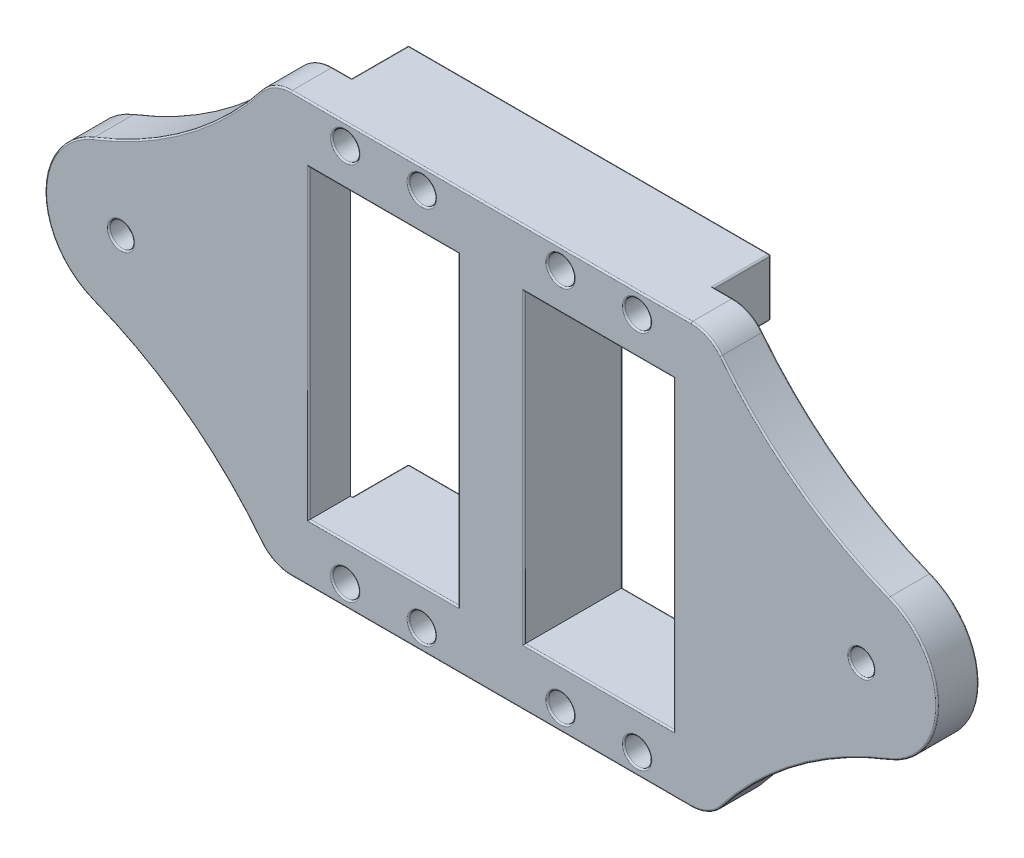
SolidWorks part; units mm, degrees
ref_plane "정면" through (0, 0, 0) normal (0, 0, 1) x (1, 0, 0)
ref_plane "윗면" through (0, 0, 0) normal (0, 1, 0) x (1, 0, 0)
ref_plane "우측면" through (0, 0, 0) normal (1, 0, 0) x (0, 0, -1)
sketch "스케치1" plane through (0, 0, 0) normal (0, 0, 1) x (1, 0, 0)
  line L0 (0, 0) -> (37.5737, 0) construction
  line L1 (4.5, -20) -> (4.5, 20)
  line L2 (4.5, 20) -> (23.9, 20)
  line L3 (4.5, -20) -> (23.9, -20)
  line L4 (23.9, 20) -> (23.9, 27.7)
  line L5 (23.9, -20) -> (23.9, -27.7)
  line L6 (23.9, 27.7) -> (-23.9, 27.7)
  line L7 (23.9, -27.7) -> (-23.9, -27.7)
  line L8 (0, -34.9912) -> (0, 34.9912) construction
  line L9 (-23.9, -20) -> (-23.9, -27.7)
  line L10 (-4.5, -20) -> (-23.9, -20)
  line L11 (-23.9, 20) -> (-23.9, 27.7)
  line L12 (-4.5, 20) -> (-23.9, 20)
  line L13 (-4.5, -20) -> (-4.5, 20)
  circle A0 centre (19.25, 25) radius 1.1
  circle A1 centre (19.25, -25) radius 1.1
  circle A2 centre (9.15, 25) radius 1.1
  circle A3 centre (9.15, -25) radius 1.1
  circle A4 centre (-9.15, -25) radius 1.1
  circle A5 centre (-19.25, -25) radius 1.1
  circle A6 centre (-19.25, 25) radius 1.1
  circle A7 centre (-9.15, 25) radius 1.1
  point P6 (4.5, 0)
  point P29 (0, -27.7)
  point P37 (0, 27.7)
  dimension "D5" = 2.2
  dimension "D7" = 4.65
  dimension "D8" = 10.1
  dimension "D1" = 40
  dimension "D2" = 19.4
  dimension "D3" = 4.5
  dimension "D4" = 7.7
  dimension "D6" = 2.7
extrude "보스-돌출1" add sketch "스케치1" along normal blind 7.5 contours L13 L10 L9 L7 L5 L3 L1 L2 L4 L6 L11 L12 A6 A5 A4 A1 A0 A2 A3 A7
sketch "스케치2" plane through (0, 0, 7.5) normal (0, 0, 1) x (1, 0, 0)
  line L0 (19.25, -25) -> (9.15, -25) construction
  line L1 (14.2, -25) -> (14.2, 33.3794) construction
  line L2 (-23.9, -27.7) -> (-26.3991, -27.7)
  line L3 (4.5, 0) -> (84.5955, 0) construction
  line L4 (4.5, -20) -> (4.5, 20) construction
  line L5 (23.9, 27.7) -> (26.3991, 27.7)
  line L6 (23.9, -27.7) -> (26.3991, -27.7)
  line L7 (23.9, 27.7) -> (23.9, -20)
  line L8 (0, 0) -> (0, 40.7303) construction
  line L9 (-23.9, 27.7) -> (-26.3991, 27.7)
  line L11 (-23.9, 20) -> (-23.9, -20)
  line L12 (14.2, -10.12) -> (48.8525, 0) construction
  line L17 (-4.5, 20) -> (-4.5, -20)
  line L18 (-4.5, -20) -> (-23.9, -20)
  line L19 (-23.9, -20) -> (-23.9, -27.7)
  line L20 (-23.9, -27.7) -> (23.9, -27.7)
  line L21 (23.9, -27.7) -> (23.9, -20)
  line L22 (23.9, -20) -> (4.5, -20)
  line L23 (4.5, -20) -> (4.5, 20)
  line L24 (4.5, 20) -> (23.9, 20)
  line L25 (23.9, 20) -> (23.9, 27.7)
  line L26 (23.9, 27.7) -> (-23.9, 27.7)
  line L27 (-23.9, 27.7) -> (-23.9, 20)
  line L28 (-23.9, 20) -> (-4.5, 20)
  line L29 (-4.5, 20) -> (-4.5, -20)
  line L30 (-4.5, -20) -> (-23.9, -20)
  line L31 (-23.9, -20) -> (-23.9, -27.7)
  line L32 (-23.9, -27.7) -> (23.9, -27.7)
  line L33 (23.9, -27.7) -> (23.9, -20)
  line L34 (23.9, -20) -> (4.5, -20)
  line L35 (4.5, -20) -> (4.5, 20)
  line L36 (4.5, 20) -> (23.9, 20)
  line L37 (23.9, 20) -> (23.9, 27.7)
  line L38 (23.9, 27.7) -> (-23.9, 27.7)
  line L39 (-23.9, 27.7) -> (-23.9, 20)
  line L40 (-23.9, 20) -> (-4.5, 20)
  circle A0 centre (14.2, -10.12) radius 9 construction
  circle A1 centre (48.8525, 0) radius 27 construction
  circle A2 centre (19.25, -25) radius 1.1 construction
  circle A3 centre (9.15, -25) radius 1.1 construction
  circle A4 centre (-9.15, -25) radius 1.1 construction
  circle A5 centre (-19.25, -25) radius 1.1 construction
  circle A6 centre (19.25, 25) radius 1.1 construction
  circle A7 centre (9.15, 25) radius 1.1 construction
  circle A8 centre (-9.15, 25) radius 1.1 construction
  circle A9 centre (-19.25, 25) radius 1.1 construction
  circle A10 centre (19.25, -25) radius 1.1
  circle A11 centre (9.15, -25) radius 1.1
  circle A12 centre (-9.15, -25) radius 1.1
  circle A13 centre (-19.25, -25) radius 1.1
  circle A14 centre (19.25, 25) radius 1.1
  circle A15 centre (9.15, 25) radius 1.1
  circle A16 centre (-9.15, 25) radius 1.1
  circle A17 centre (-19.25, 25) radius 1.1
  circle A18 centre (48.8525, 0) radius 1.6
  circle A21 centre (-48.8525, 0) radius 1.6
  arc A24 (52.497, -9.3122) -> (30.3323, -25.7871) centre (71.6307, -58.2014) ccw
  arc A25 (52.497, -9.3122) -> (52.497, 9.3122) centre (48.8525, 0) ccw
  arc A26 (52.497, 9.3122) -> (30.3323, 25.7871) centre (71.6307, 58.2014) cw
  arc A27 (26.3991, -27.7) -> (30.3323, -25.7871) centre (26.3991, -22.7) ccw
  arc A28 (26.3991, 27.7) -> (30.3323, 25.7871) centre (26.3991, 22.7) cw
  arc A29 (-26.3991, -27.7) -> (-30.3323, -25.7871) centre (-26.3991, -22.7) cw
  arc A30 (-52.497, -9.3122) -> (-30.3323, -25.7871) centre (-71.6307, -58.2014) cw
  arc A31 (-52.497, -9.3122) -> (-52.497, 9.3122) centre (-48.8525, 0) cw
  arc A32 (-52.497, 9.3122) -> (-30.3323, 25.7871) centre (-71.6307, 58.2014) ccw
  arc A33 (-26.3991, 27.7) -> (-30.3323, 25.7871) centre (-26.3991, 22.7) ccw
  point P54 (0, 0)
  point P65 (71.443, -57.9605)
  point P66 (72.0194, -58.7003)
  point P69 (28.9, -27.7)
  point P72 (28.9, 27.7)
  dimension "D2" = 18
  dimension "D3" = 54
  dimension "D6" = 3.2
  dimension "D7" = 71.6307
  dimension "D8" = 5
  dimension "D10" = 105
  dimension "D11" = 10
  dimension "D9" = 5
  dimension "D1" = 14.88
  dimension "D4" = 36.1
  dimension "D5" = 0
extrude "보스-돌출2" add sketch "스케치2" along normal blind 5.5
sketch "스케치3" plane through (0, 0, 7.5) normal (0, 0, -1) x (-1, 0, 0)
  line L0 (0, 0) -> (0, 34.0437) construction
  line L2 (-48.8525, -3.18) -> (-46.0985, -1.59)
  line L3 (48.8525, -3.18) -> (46.0985, -1.59)
  line L4 (-46.0985, -1.59) -> (-46.0985, 1.59)
  line L5 (46.0985, -1.59) -> (46.0985, 1.59)
  line L6 (-46.0985, 1.59) -> (-48.8525, 3.18)
  line L7 (46.0985, 1.59) -> (48.8525, 3.18)
  line L8 (-48.8525, 3.18) -> (-51.6065, 1.59)
  line L9 (48.8525, 3.18) -> (51.6065, 1.59)
  line L10 (-51.6065, 1.59) -> (-51.6065, -1.59)
  line L11 (51.6065, 1.59) -> (51.6065, -1.59)
  line L12 (-51.6065, -1.59) -> (-48.8525, -3.18)
  line L13 (51.6065, -1.59) -> (48.8525, -3.18)
  circle A0 centre (-48.8525, 0) radius 2.754 construction
  dimension "D1" = 3.18
extrude "컷-돌출1" cut sketch "스케치3" against normal blind 3
sketch "스케치4" plane through (0, 0, 13) normal (0, 0, 1) x (1, 0, 0)
  circle A0 centre (-19.25, 25) radius 1.75
  circle A1 centre (-9.15, 25) radius 1.75
  circle A2 centre (9.15, 25) radius 1.75
  circle A3 centre (19.25, 25) radius 1.75
  circle A4 centre (-19.25, -25) radius 1.75
  circle A5 centre (-9.15, -25) radius 1.75
  circle A6 centre (9.15, -25) radius 1.75
  circle A7 centre (19.25, -25) radius 1.75
  dimension "D1" = 3.5
extrude "컷-돌출2" cut sketch "스케치4" against normal blind 3
sketch "스케치5" plane through (0, 0, 13) normal (0, 0, 1) x (1, 0, 0)
  line L0 (4.5, 20) -> (23.9, 20) construction
  line L1 (4.5, -20) -> (4.5, 20) construction
  line L2 (23.9, -20) -> (23.9, 20) construction
  line L3 (23.9, -20) -> (4.5, -20) construction
  line L4 (-4.5, -20) -> (-23.9, -20) construction
  line L5 (-23.9, 20) -> (-23.9, -20) construction
  line L6 (-23.9, 20) -> (-4.5, 20) construction
  line L7 (-4.5, 20) -> (-4.5, -20) construction
  line L8 (4.5, 20) -> (23.9, 20)
  line L9 (4.5, -20) -> (4.5, 20)
  line L10 (23.9, -20) -> (23.9, 20)
  line L11 (23.9, -20) -> (4.5, -20)
  line L12 (-4.5, -20) -> (-23.9, -20)
  line L13 (-23.9, 20) -> (-23.9, -20)
  line L14 (-23.9, 20) -> (-4.5, 20)
  line L15 (-4.5, 20) -> (-4.5, -20)
  line L16 (-24.05, 20.15) -> (-4.35, 20.15)
  line L17 (-4.35, 20.15) -> (-4.35, -20.15)
  line L18 (-4.35, -20.15) -> (-24.05, -20.15)
  line L19 (-24.05, 20.15) -> (-24.05, -20.15)
  line L20 (4.35, 20.15) -> (24.05, 20.15)
  line L21 (24.05, -20.15) -> (24.05, 20.15)
  line L22 (24.05, -20.15) -> (4.35, -20.15)
  line L23 (4.35, -20.15) -> (4.35, 20.15)
  line M17 (23.9, 20) -> (23.9, -20)
  line M18 (23.9, -20) -> (4.5, -20)
  line M19 (4.5, -20) -> (4.5, 20)
  line M20 (4.5, 20) -> (23.9, 20)
  line M21 (-23.9, -20) -> (-23.9, 20)
  line M22 (-23.9, 20) -> (-4.5, 20)
  line M23 (-4.5, 20) -> (-4.5, -20)
  line M24 (-4.5, -20) -> (-23.9, -20)
  dimension "D1" = 0.15
  dimension "D2" = 0.15
extrude "컷-돌출3" cut sketch "스케치5" against normal through all contours L16 L19 L18 L17 M24 M21 M22 M23 | L23 L22 L21 L20 M20 M17 M18 M19 | L14 L15 L12 L13
fillet "필렛1" radius 0.2 94 edges at (-25.1495, 27.7, 7.5) (-28.5859, 27.1964, 7.5) (-40.3119, 16.0661, 7.5) (-58.8525, 0, 7.5) (-25.1495, -27.7, 7.5) (-28.5859, -27.1964, 7.5) (25.1495, -27.7, 7.5) (28.5859, -27.1964, 7.5) (40.3119, -16.0661, 7.5) (58.8525, 0, 7.5) (25.1495, 27.7, 7.5) (28.5859, 27.1964, 7.5) (20.35, -25, 10) (10.25, -25, 10) (-8.05, -25, 10) (-18.15, -25, 10) (-18.15, 25, 10) (-8.05, 25, 10) (10.25, 25, 10) (20.35, 25, 10) (-47.2525, 0, 10.5) (47.2525, 0, 10.5) (-4.35, 0, 0) (-14.125, -20.15, 0) (-23.9, -23.925, 0) (0, -27.7, 0) (23.9, -23.925, 0) (14.125, -20.15, 0) (4.35, 0, 0) (14.125, 20.15, 0) (23.9, 23.925, 0) (0, 27.7, 0) (-23.9, 23.925, 0) (-14.125, 20.15, 0) (-8.05, 25, 0) (10.25, -25, 0) (10.25, 25, 0) (20.35, 25, 0) (20.35, -25, 0) (-8.05, -25, 0) (-18.15, -25, 0) (-18.15, 25, 0) (-14.2, -20.15, 13) (-4.35, 0, 13) (-14.2, 20.15, 13) (-24.05, 0, 13) (50.4525, 0, 13) (28.5859, 27.1964, 13) (40.3119, 16.0661, 13) (58.8525, 0, 13) (40.3119, -16.0661, 13) (28.5859, -27.1964, 13) (0, -27.7, 13) (-28.5859, -27.1964, 13) (-40.3119, -16.0661, 13) (-58.8525, 0, 13) (-40.3119, 16.0661, 13) (-28.5859, 27.1964, 13) (0, 27.7, 13) (-47.2525, 0, 13) (-17.5, 25, 13) (21, -25, 13) (10.9, -25, 13) (-7.4, -25, 13) (-7.4, 25, 13) (10.9, 25, 13) (21, 25, 13) (-17.5, -25, 13) (24.05, 0, 13) (14.2, 20.15, 13) (4.35, 0, 13) (14.2, -20.15, 13) (-23.9, 27.7, 3.75) (23.9, 27.7, 3.75) (23.9, -27.7, 3.75) (-23.9, -27.7, 3.75) (-23.9, -20.15, 3.75) (-23.9, 20.15, 3.75) (23.9, -20.15, 3.75) (23.9, 20.15, 3.75) (-46.0985, 0, 7.5) (-47.4755, -2.385, 7.5) (-50.2295, -2.385, 7.5) (-51.6065, 0, 7.5) (-50.2295, 2.385, 7.5) (-47.4755, 2.385, 7.5) (51.6065, 0, 7.5) (50.2295, -2.385, 7.5) (47.4755, -2.385, 7.5) (46.0985, 0, 7.5) (47.4755, 2.385, 7.5) (50.2295, 2.385, 7.5) (-40.3119, -16.0661, 7.5) (40.3119, 16.0661, 7.5)
